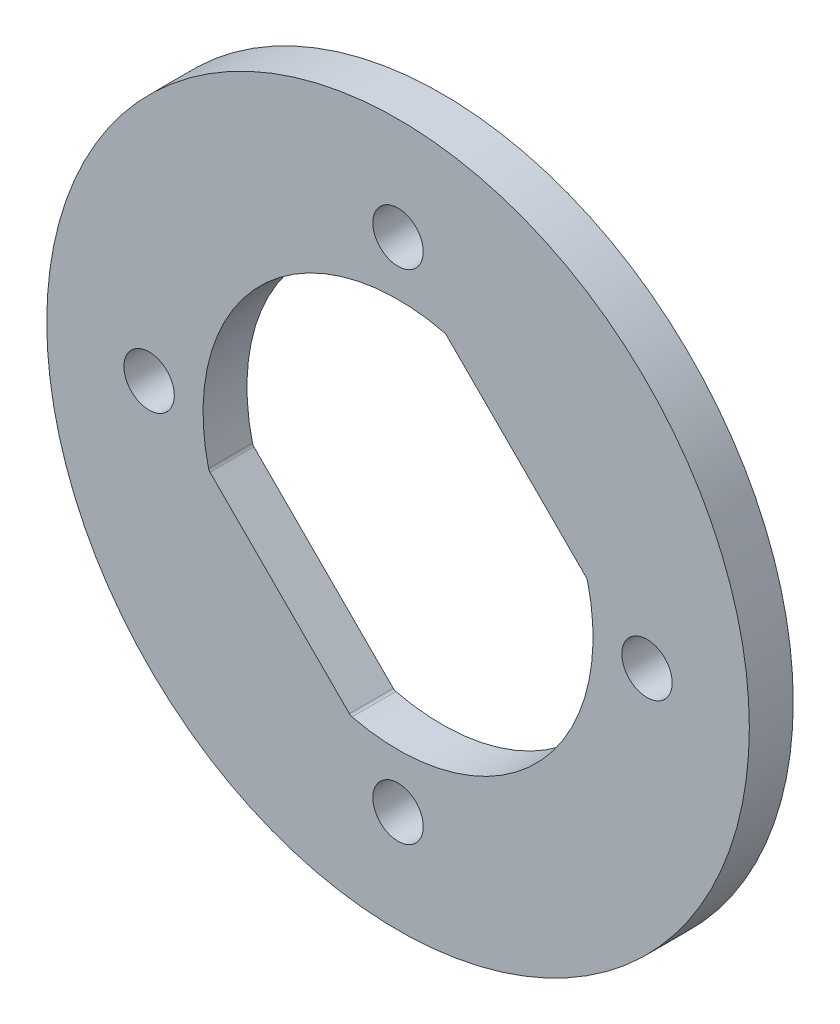
SolidWorks part; units mm, degrees
ref_plane "Front Plane" through (0, 0, 0) normal (0, 0, 1) x (1, 0, 0)
ref_plane "Top Plane" through (0, 0, 0) normal (0, 1, 0) x (1, 0, 0)
ref_plane "Right Plane" through (0, 0, 0) normal (1, 0, 0) x (0, 0, -1)
sketch "Sketch6" plane through (0, 0, 0) normal (0, 0, 1) x (1, 0, 0)
  line L0 (6.7979, 1.7581) -> (1.7581, 6.7979)
  line L1 (-6.7979, -1.7581) -> (-1.7581, -6.7979)
  line L2 (-6.2696, 8.8858) -> (-5.0558, 7.6721)
  line L3 (-7.6721, 5.0558) -> (-8.8858, 6.2696)
  line L4 (-8.8858, -6.2696) -> (-7.6721, -5.0558)
  line L5 (-5.0558, -7.6721) -> (-6.2696, -8.8858)
  line L6 (6.2696, -8.8858) -> (5.0558, -7.6721)
  line L7 (7.6721, -5.0558) -> (8.8858, -6.2696)
  line L8 (8.8858, 6.2696) -> (7.6721, 5.0558)
  line L9 (5.0558, 7.6721) -> (6.2696, 8.8858)
  arc A0 (-7.6721, 5.0558) -> (-5.0558, 7.6721) centre (-6.364, 6.364) ccw
  arc A1 (-8.8858, 6.2696) -> (-8.8858, -6.2696) centre (0, 0) ccw
  arc A2 (-5.0558, -7.6721) -> (-7.6721, -5.0558) centre (-6.364, -6.364) ccw
  arc A3 (-6.2696, -8.8858) -> (6.2696, -8.8858) centre (0, 0) ccw
  arc A4 (7.6721, -5.0558) -> (5.0558, -7.6721) centre (6.364, -6.364) ccw
  arc A5 (8.8858, -6.2696) -> (8.8858, 6.2696) centre (0, 0) ccw
  arc A6 (5.0558, 7.6721) -> (7.6721, 5.0558) centre (6.364, 6.364) ccw
  arc A7 (6.2696, 8.8858) -> (-6.2696, 8.8858) centre (0, 0) ccw
  arc A8 (6.8508, 1.6639) -> (6.7979, 1.7581) centre (6.6565, 1.6167) ccw
  arc A9 (1.7581, 6.7979) -> (1.6639, 6.8508) centre (1.6167, 6.6565) ccw
  arc A10 (-6.8508, -1.6639) -> (-6.7979, -1.7581) centre (-6.6565, -1.6167) ccw
  arc A11 (1.6639, 6.8508) -> (-6.8508, -1.6639) centre (0, 0) ccw
  arc A12 (-1.7581, -6.7979) -> (-1.6639, -6.8508) centre (-1.6167, -6.6565) ccw
  arc A13 (-1.6639, -6.8508) -> (6.8508, 1.6639) centre (0, 0) ccw
  circle A14 centre (-9, 0) radius 0.9115
  circle A15 centre (0, -9) radius 0.9115
  circle A16 centre (9, 0) radius 0.9115
  circle A17 centre (0, 9) radius 0.9115
  circle A18 centre (0, 0) radius 12.7
  dimension "D1" = 1.823
  dimension "D2" = 25.4
extrude "Boss-Extrude3" add sketch "Sketch6" along normal blind 1.5875 contours A18 A7 L9 A6 L8 A5 L7 A4 L6 A3 L5 A2 L4 A1 L3 A0 L2 | L9 A7 L2 A0 L3 A1 L4 A2 L5 A3 L6 A4 L7 A5 L8 A6 A17 A16 A15 A14 A13 A12 L1 A10 A11 A9 L0 A8
